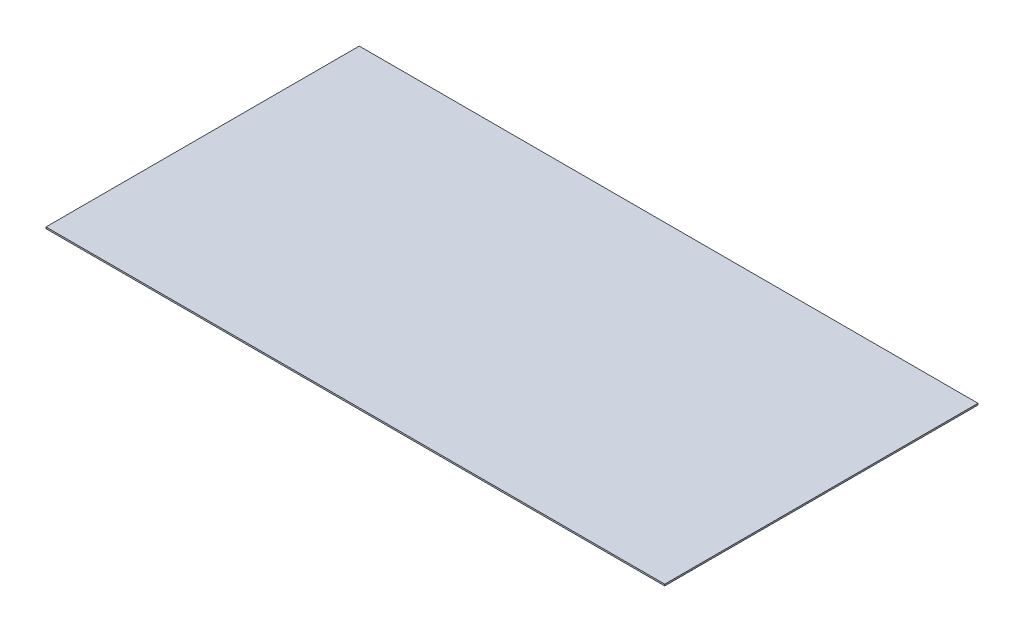
SolidWorks part; units mm, degrees
ref_plane "Front" through (0, 0, 0) normal (0, 0, 1) x (1, 0, 0)
ref_plane "Top" through (0, 0, 0) normal (0, 1, 0) x (1, 0, 0)
ref_plane "Right" through (0, 0, 0) normal (1, 0, 0) x (0, 0, -1)
sketch "Sketch1" plane through (0, 0, 0) normal (0, 1, 0) x (1, 0, 0)
  line L0 (-74.0058, 0) -> (323.2879, 0) construction
  line L1 (0, 100) -> (395, 100)
  line L2 (0, 100) -> (0, -100)
  line L3 (0, -100) -> (395, -100)
  line L4 (395, 100) -> (395, -100)
  dimension "D1" = 395
  dimension "D2" = 200
extrude "Cut-Extrude1" add sketch "Sketch1" along normal blind 1 separate body
